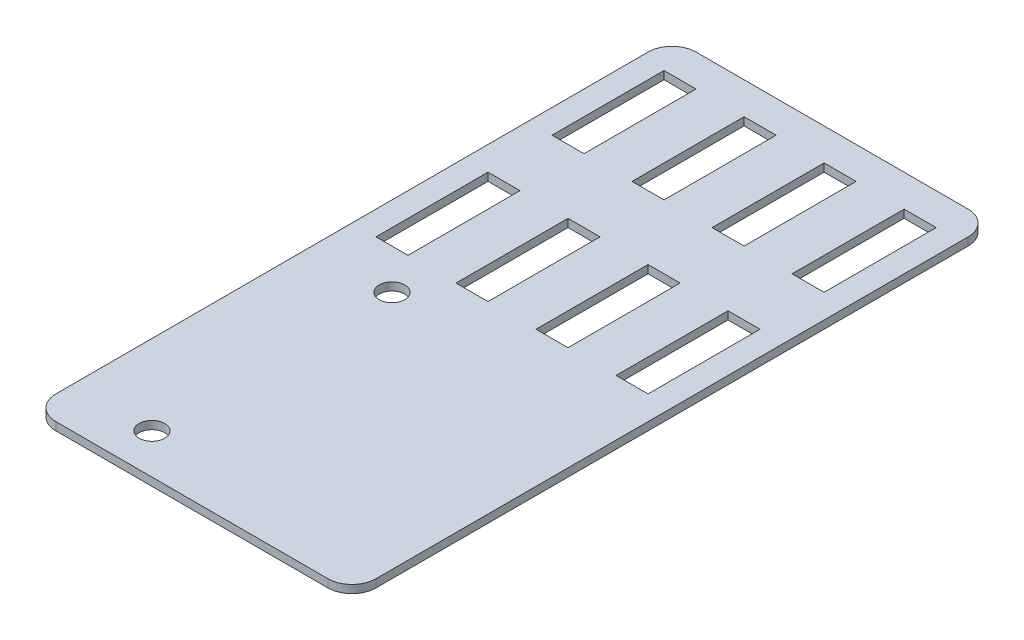
SolidWorks part; units mm, degrees
material "碳板"
ref_plane "前视基准面" through (0, 0, 0) normal (0, 0, 1) x (1, 0, 0)
ref_plane "上视基准面" through (0, 0, 0) normal (0, 1, 0) x (1, 0, 0)
ref_plane "右视基准面" through (0, 0, 0) normal (1, 0, 0) x (0, 0, -1)
sketch "草图1" plane through (0, 0, 0) normal (0, 1, 0) x (1, 0, 0)
  line L0 (-46.6667, -20) -> (45.5285, -20) construction
  line L1 (-20, 40) -> (20, 40)
  line L2 (-20, 40) -> (-20, -40)
  line L3 (-20, -40) -> (20, -40)
  line L4 (20, 40) -> (20, -40)
  line L5 (-20, 40) -> (20, -40) construction
  line L6 (-20, -40) -> (20, 40) construction
  line L7 (0, 49.3856) -> (0, -55.8827) construction
  line L8 (-7, 14) -> (-7, 0)
  line L9 (-17, 14) -> (-13, 14)
  line L10 (-17, 14) -> (-17, 0)
  line L11 (-17, 0) -> (-13, 0)
  line L12 (-13, 14) -> (-13, 0)
  line L13 (-17, 14) -> (-13, 0) construction
  line L14 (-17, 0) -> (-13, 14) construction
  line L15 (-7, 14) -> (-3, 14)
  line L16 (-3, 14) -> (-3, 0)
  line L17 (-7, 0) -> (-3, 0)
  line L18 (3, 14) -> (3, 0)
  line L19 (3, 14) -> (7, 14)
  line L20 (7, 14) -> (7, 0)
  line L21 (3, 0) -> (7, 0)
  line L22 (13, 14) -> (13, 0)
  line L23 (13, 14) -> (17, 14)
  line L24 (17, 14) -> (17, 0)
  line L25 (13, 0) -> (17, 0)
  line L26 (-7, 36) -> (-7, 22)
  line L27 (-7, 36) -> (-3, 36)
  line L28 (-3, 36) -> (-3, 22)
  line L29 (-7, 22) -> (-3, 22)
  line L30 (3, 36) -> (3, 22)
  line L31 (3, 36) -> (7, 36)
  line L32 (7, 36) -> (7, 22)
  line L33 (3, 22) -> (7, 22)
  line L34 (13, 36) -> (13, 22)
  line L35 (13, 36) -> (17, 36)
  line L36 (17, 36) -> (17, 22)
  line L37 (13, 22) -> (17, 22)
  line L38 (-17, 36) -> (-17, 22)
  line L39 (-17, 36) -> (-13, 36)
  line L40 (-13, 36) -> (-13, 22)
  line L41 (-17, 22) -> (-13, 22)
  line L42 (-17, 14) -> (-7, 14) construction
  circle A0 centre (-10, -35) radius 1.6
  circle A1 centre (-10, -5) radius 1.6
  point P0 (0, 0)
  point P14 (-15, 7)
  point P19 (-15, 22)
  dimension "D4" = 30
  dimension "D5" = 3.2
  dimension "D1" = 40
  dimension "D2" = 80
  dimension "D3" = 20
  dimension "D6" = 10
  dimension "D7" = 4
  dimension "D8" = 14
  dimension "D9" = 20
  dimension "D10" = 3
  dimension "D13" = 10
  dimension "D14" = 8
  dimension "D11" = 4
  dimension "D12" = 2
extrude "凸台-拉伸1" add sketch "草图1" along normal blind 1
fillet "圆角1" radius 3 4 edges at (20, 0.5, 40) (-20, 0.5, -40) (20, 0.5, -40) (-20, 0.5, 40)
